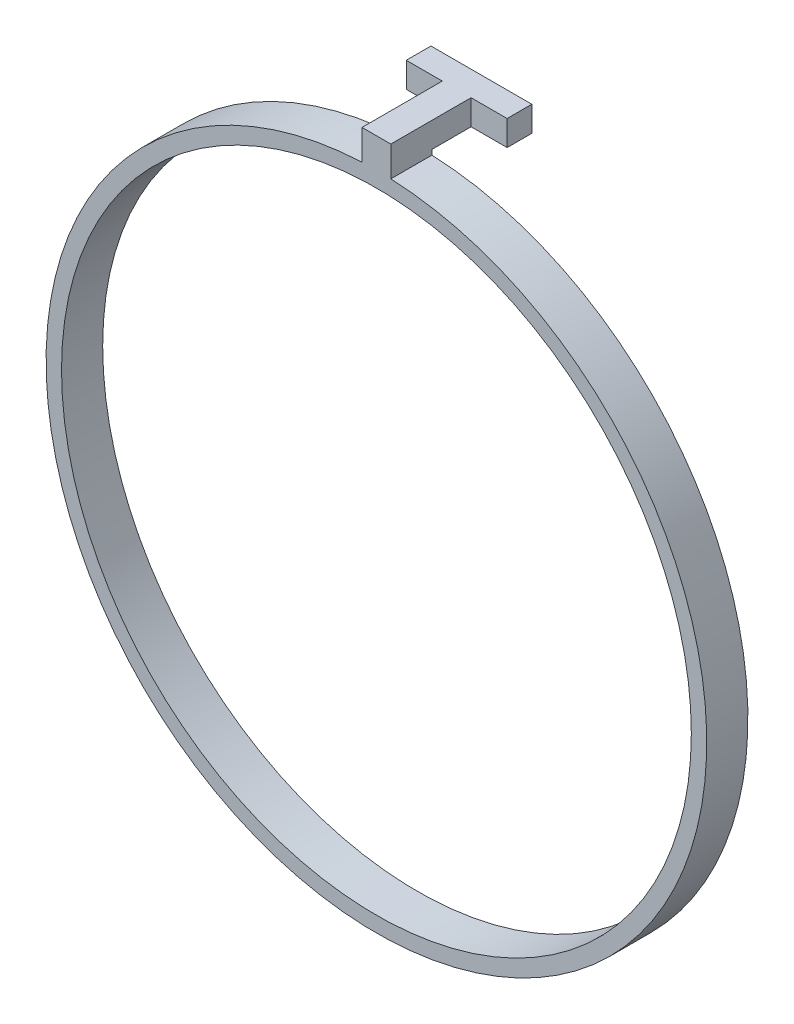
SolidWorks part; units mm, degrees
ref_plane "Front Plane" through (0, 0, 0) normal (0, 0, 1) x (1, 0, 0)
ref_plane "Top Plane" through (0, 0, 0) normal (0, 1, 0) x (1, 0, 0)
ref_plane "Right Plane" through (0, 0, 0) normal (1, 0, 0) x (0, 0, -1)
sketch "Sketch2" plane through (0, 0, 0) normal (0, 0, 1) x (1, 0, 0)
  line L0 (0, 0) -> (0, 32.1) construction
  line L2 (-1.4, 35) -> (1.4, 35)
  line L3 (-1.4, 35) -> (-1.4, 32.0695)
  line L5 (1.4, 35) -> (1.4, 32.0695)
  line L6 (-1.4, 35) -> (1.4, 29.2) construction
  line L7 (-1.4, 29.2) -> (1.4, 35) construction
  circle A0 centre (0, 0) radius 30.6
  arc A1 (-1.4, 32.0695) -> (1.4, 32.0695) centre (0, 0) ccw
  dimension "D1" = 61.2
  dimension "D2" = 64.2
  dimension "D3" = 2.8
  dimension "D4" = 35
extrude "Boss-Extrude1" add sketch "Sketch2" along normal blind 4
sketch "Sketch3" plane through (0, 0, 0) normal (0, 0, -1) x (-1, 0, 0)
  line L1 (-1.4, 35) -> (1.4, 35)
  line L2 (-1.4, 35) -> (-1.4, 32.55)
  line L3 (-1.4, 32.55) -> (1.4, 32.55)
  line L4 (1.4, 35) -> (1.4, 32.55)
  dimension "D1" = 2.45
  dimension "D2" = 2.8
extrude "Boss-Extrude2" add sketch "Sketch3" along normal blind 3.8
sketch "Sketch4" plane through (1.4, 0, 0) normal (1, 0, 0) x (0, 0, -1)
  line L1 (3.8, 35) -> (6.2, 35)
  line L2 (3.8, 35) -> (3.8, 32.55)
  line L3 (3.8, 32.55) -> (6.2, 32.55)
  line L4 (6.2, 35) -> (6.2, 32.55)
  dimension "D1" = 2.4
  dimension "D2" = 2.45
extrude "Boss-Extrude3" add sketch "Sketch4" along normal blind 9.8 from offset 6.3 offset against normal yes
